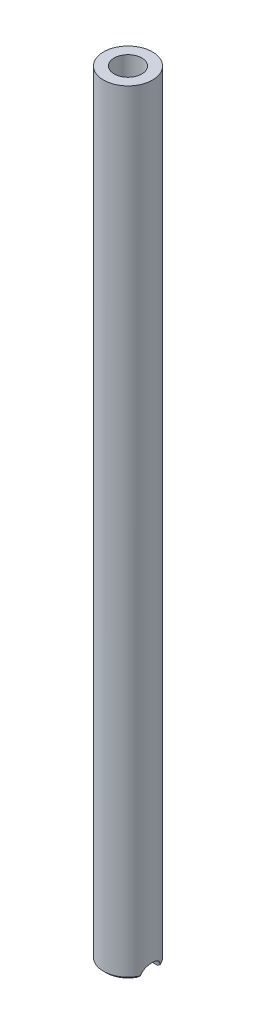
SolidWorks part; units mm, degrees
ref_plane "Front Plane" through (0, 0, 0) normal (0, 0, 1) x (1, 0, 0)
ref_plane "Top Plane" through (0, 0, 0) normal (0, 1, 0) x (1, 0, 0)
ref_plane "Right Plane" through (0, 0, 0) normal (1, 0, 0) x (0, 0, -1)
sketch "Sketch1" plane through (0, 0, 0) normal (0, 1, 0) x (1, 0, 0)
  circle A0 centre (0, 0) radius 3
  dimension "D1" = 6
extrude "Boss-Extrude1" add sketch "Sketch1" along normal blind 95
sketch "Sketch2" plane through (0, 95, 0) normal (0, 1, 0) x (1, 0, 0)
  circle A0 centre (0, 0) radius 1.7
  dimension "D1" = 3.4
extrude "Cut-Extrude1" cut sketch "Sketch2" against normal through all
chamfer "Chamfer1" distance 0.3 angle 45 1 edges at (0, 0, 3)
sketch "Sketch3" plane through (0, 0, 0) normal (1, 0, 0) x (0, 0, -1)
  circle A0 centre (0, 0) radius 1.25
  dimension "D1" = 2.5
extrude "Cut-Extrude2" cut sketch "Sketch3" against normal through all both and the other way through all
